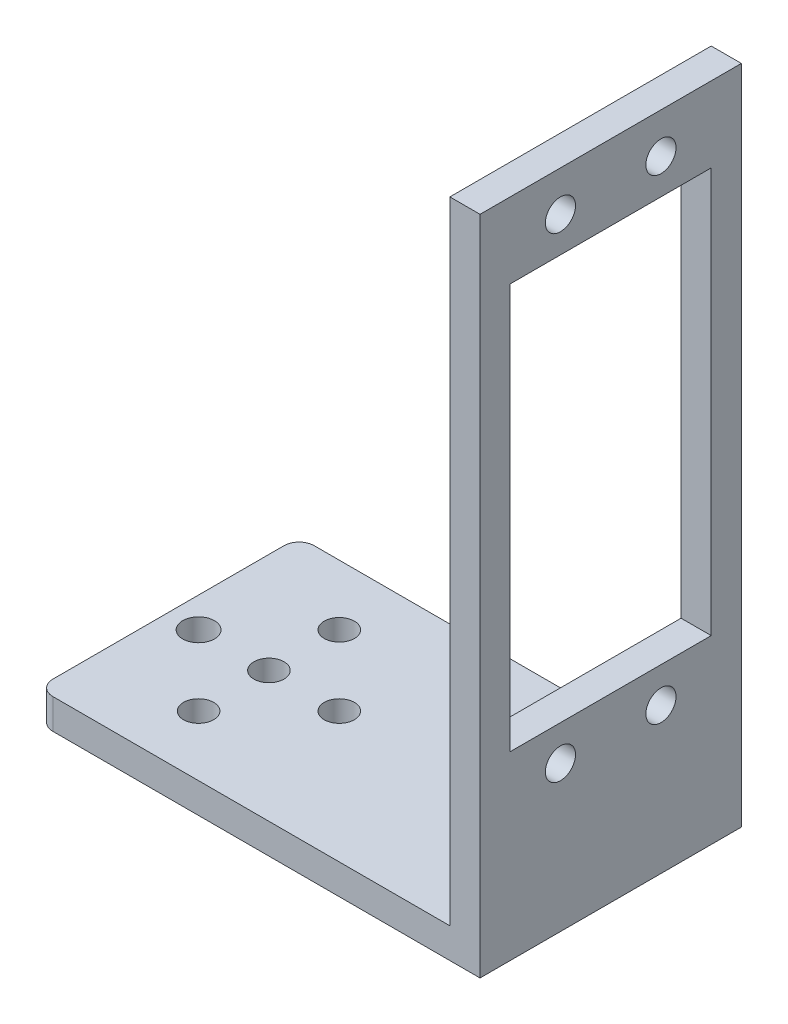
SolidWorks part; units mm, degrees
ref_plane "Alzado" through (0, 0, 0) normal (0, 0, 1) x (1, 0, 0)
ref_plane "Planta" through (0, 0, 0) normal (0, 1, 0) x (1, 0, 0)
ref_plane "Vista lateral" through (0, 0, 0) normal (1, 0, 0) x (0, 0, -1)
sketch "Croquis1" plane through (0, 0, 0) normal (0, 1, 0) x (1, 0, 0)
  line L0 (0, 1.5) -> (0, 24.5)
  line L1 (1.5, 26) -> (44, 26)
  line L2 (44, 26) -> (44, 0)
  line L3 (44, 0) -> (1.5, 0)
  line L4 (22.75, 0) -> (22.75, 26) construction
  line L5 (44, 13) -> (10, 13) construction
  circle A0 centre (10, 13) radius 1.5
  circle A1 centre (17, 13) radius 1.5
  circle A2 centre (10, 20) radius 1.5
  circle A3 centre (10, 6) radius 1.5
  circle A4 centre (3, 13) radius 1.58
  arc A5 (0, 24.5) -> (1.5, 26) centre (1.5, 24.5) cw
  arc A6 (0, 1.5) -> (1.5, 0) centre (1.5, 1.5) ccw
  point P20 (0, 26)
  point P23 (0, 0)
  dimension "D4" = 7
  dimension "D8" = 1.5
  dimension "D1" = 26
  dimension "D2" = 44
  dimension "D3" = 34
  dimension "D5" = 7
  dimension "D6" = 7
  dimension "D7" = 7
extrude "Saliente-Extruir1" add sketch "Croquis1" along normal blind 3
sketch "Croquis2" plane through (0, 3, 0) normal (0, 1, 0) x (1, 0, 0)
  line L0 (44, 0) -> (41, 0)
  line L1 (1.5, 0) -> (44, 0) construction
  line L2 (41, 0) -> (41, 26)
  line L3 (44, 26) -> (1.5, 26) construction
  line L4 (41, 26) -> (44, 26)
  line L5 (44, 26) -> (44, 0)
  dimension "D1" = 3
extrude "Saliente-Extruir2" add sketch "Croquis2" along normal blind 15
sketch "Croquis3" plane through (41, 0, 0) normal (-1, 0, 0) x (0, 0, 1)
  line L0 (-13, 18) -> (-13, 14.5) construction
  line L1 (-26, 18) -> (0, 18) construction
  line L2 (-13, 14.5) -> (-18, 14.5) construction
  circle A0 centre (-18, 14.5) radius 1.5
  circle A1 centre (-8, 14.5) radius 1.5
  dimension "D1" = 3.5
  dimension "D2" = 5
extrude "Cortar-Extruir1" cut sketch "Croquis3" against normal blind 15
sketch "Croquis4" plane through (0, 18, 0) normal (0, 1, 0) x (1, 0, 0)
  line L0 (44, 13) -> (41, 13) construction
  line L1 (44, 0) -> (44, 26) construction
  line L2 (41, 26) -> (41, 0) construction
  line L3 (44, 3) -> (44, 23)
  line L4 (44, 23) -> (41, 23)
  line L5 (41, 23) -> (41, 26)
  line L6 (41, 26) -> (44, 26)
  line L7 (44, 26) -> (44, 23)
  line L8 (44, 0) -> (44, 3)
  line L9 (41, 3) -> (41, 0)
  line L10 (41, 26) -> (41, 0) construction
  line L11 (41, 0) -> (44, 0)
  line L12 (44, 3) -> (41, 3)
  point P9 (44, 13)
  line M2 (44, 0) -> (44, 26)
  line M3 (44, 26) -> (41, 26)
  line M4 (41, 26) -> (41, 0)
  line M5 (41, 0) -> (44, 0)
  dimension "D1" = 20
extrude "Saliente-Extruir3" add sketch "Croquis4" along normal blind 40.3 contours L4 M2 M3 M4 | L12 M2 M4 M5
sketch "Croquis5" plane through (0, 58.3, 0) normal (0, 1, 0) x (1, 0, 0)
  line L0 (41, 26) -> (41, 0)
  line L1 (41, 0) -> (44, 0)
  line L2 (44, 0) -> (44, 26)
  line L3 (44, 26) -> (41, 26)
extrude "Saliente-Extruir5" add sketch "Croquis5" along normal blind 7.5
sketch "Croquis6" plane through (41, 0, 0) normal (-1, 0, 0) x (0, 0, 1)
  line L0 (-13, 58.3) -> (-13, 61.8) construction
  line L1 (-23, 58.3) -> (-3, 58.3) construction
  line L2 (-13, 61.8) -> (-18, 61.8) construction
  circle A0 centre (-18, 61.8) radius 1.5
  circle A1 centre (-8, 61.8) radius 1.5
  dimension "D1" = 3.5
  dimension "D2" = 5
extrude "Cortar-Extruir2" cut sketch "Croquis6" against normal blind 7.5
sketch "Croquis9" plane through (41, 0, 0) normal (-1, 0, 0) x (0, 0, 1)
  line L0 (-18, 14.5) -> (-18, 3) construction
  line L1 (-24.5, 3) -> (-1.5, 3) construction
  line L2 (-18, 14.5) -> (-8, 14.5) construction
  line L3 (-18, 14.5) -> (-30.3965, 15.1877) construction
  line L4 (-23, 18) -> (-3, 18) construction
  line L5 (-23, 18) -> (-23, 58.3) construction
  dimension "D1" = 20
